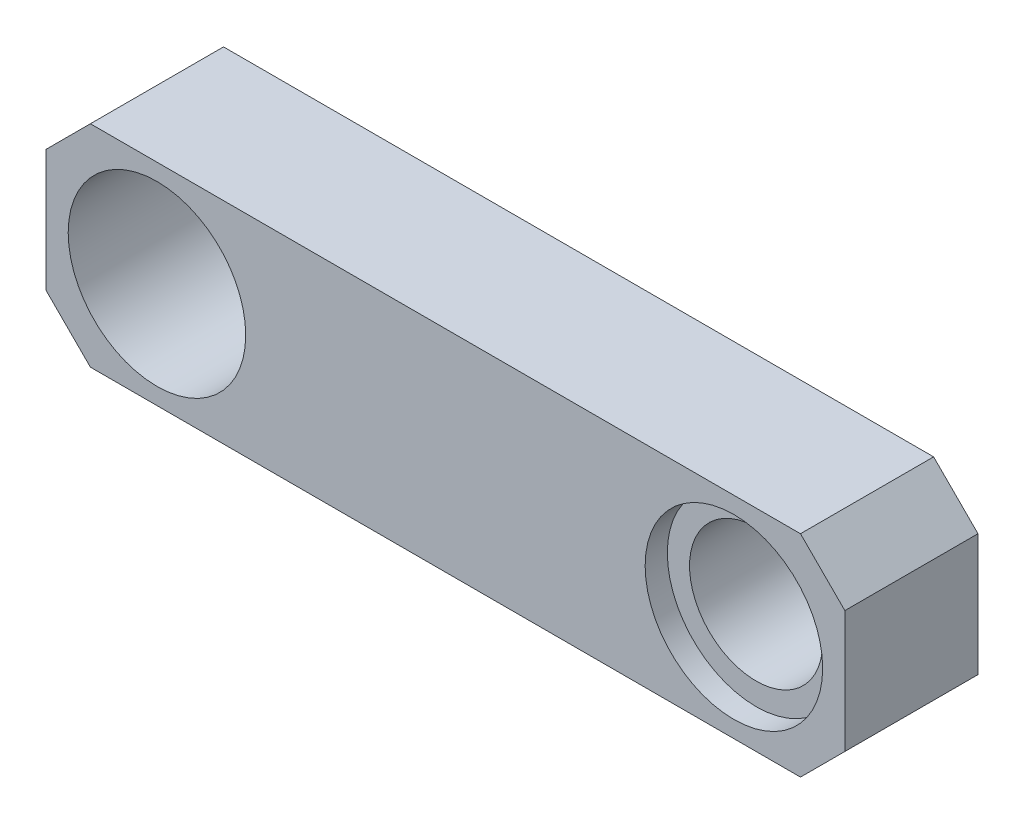
SolidWorks part; units mm, degrees
ref_plane "前视基准面" through (0, 0, 0) normal (0, 0, 1) x (1, 0, 0)
ref_plane "上视基准面" through (0, 0, 0) normal (0, 1, 0) x (1, 0, 0)
ref_plane "右视基准面" through (0, 0, 0) normal (1, 0, 0) x (0, 0, -1)
sketch "草图1" plane through (0, 0, 0) normal (0, 0, 1) x (1, 0, 0)
  line L1 (-18, -4.75) -> (18, -4.75)
  line L2 (-18, -4.75) -> (-18, 4.75)
  line L3 (-18, 4.75) -> (18, 4.75)
  line L4 (18, -4.75) -> (18, 4.75)
  line L5 (-18, -4.75) -> (18, 4.75) construction
  line L6 (-18, 4.75) -> (18, -4.75) construction
  point P0 (0, 0)
  dimension "D1" = 9.5
  dimension "D2" = 36
extrude "凸台-拉伸1" add sketch "草图1" along normal mid plane 6
sketch "草图2" plane through (0, 0, 3) normal (0, 0, 1) x (1, 0, 0)
  line L0 (-18, 4.75) -> (-18, -4.75) construction
  circle A0 centre (-13, 0) radius 4
  dimension "D1" = 8
  dimension "D2" = 5
extrude "切除-拉伸1" cut sketch "草图2" against normal through all both and the other way through all
sketch "草图3" plane through (0, 0, 3) normal (0, 0, 1) x (1, 0, 0)
  line L0 (-13, 0) -> (13, 0) construction
  circle A0 centre (13, 0) radius 4
  dimension "D2" = 8
  dimension "D1" = 26
extrude "切除-拉伸2" cut sketch "草图3" against normal blind 1 and the other way through all
sketch "草图4" plane through (0, 0, 2) normal (0, 0, 1) x (1, 0, 0)
  circle A0 centre (13, 0) radius 3
  circle A1 centre (13, 0) radius 4 construction
  dimension "D1" = 6
extrude "切除-拉伸3" cut sketch "草图4" against normal through all
chamfer "倒角1" distance 2 angle 45 4 edges at (-18, -4.75, 0) (18, -4.75, 0) (18, 4.75, 0) (-18, 4.75, 0)
